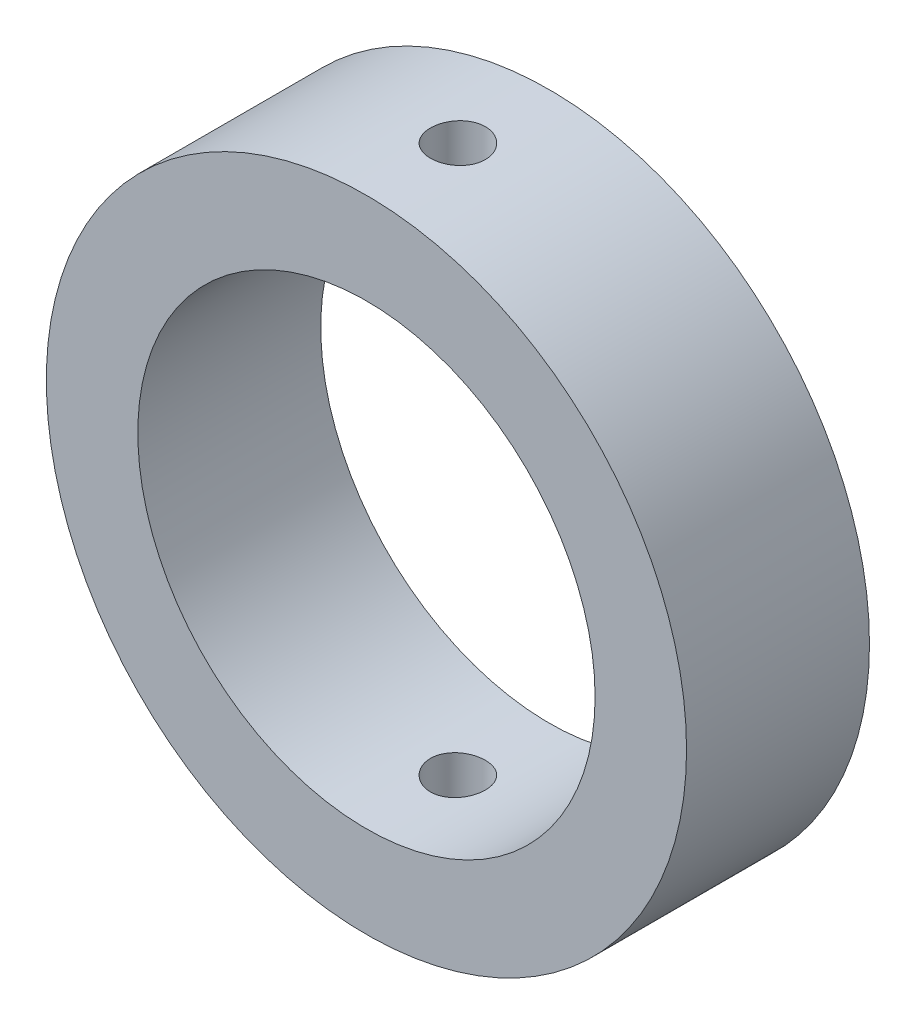
SolidWorks part; units mm, degrees
ref_plane "Front Plane" through (0, 0, 0) normal (0, 0, 1) x (1, 0, 0)
ref_plane "Top Plane" through (0, 0, 0) normal (0, 1, 0) x (1, 0, 0)
ref_plane "Right Plane" through (0, 0, 0) normal (1, 0, 0) x (0, 0, -1)
sketch "Sketch1" plane through (0, 0, 0) normal (0, 0, 1) x (1, 0, 0)
  circle A0 centre (0, 0) radius 25
  circle A1 centre (0, 0) radius 35
  dimension "D1" = 70
  dimension "D2" = 50
extrude "Boss-Extrude1" add sketch "Sketch1" along normal blind 20
sketch "Sketch2" plane through (0, 0, 0) normal (0, 1, 0) x (1, 0, 0)
  circle A0 centre (0, -10) radius 3
  point P2 (0, 0)
  dimension "D1" = 6
  dimension "D2" = 10
extrude "Cut-Extrude1" cut sketch "Sketch2" against normal through all both and the other way through all
